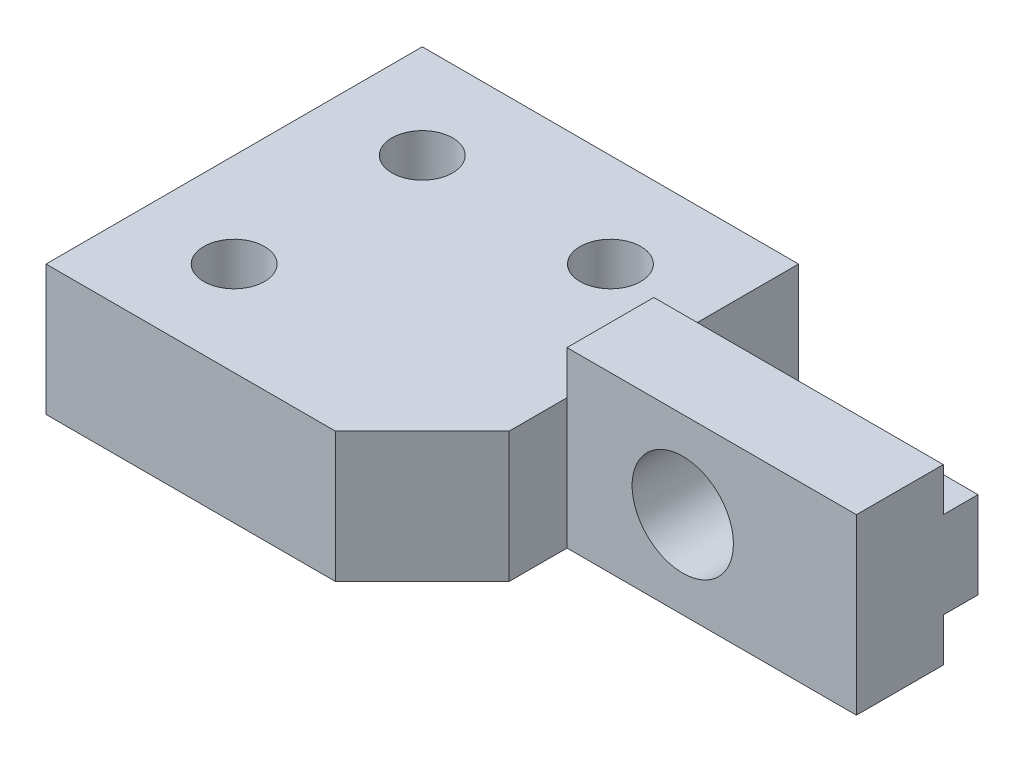
SolidWorks part; units mm, degrees
ref_plane "前视基准面" through (0, 0, 0) normal (0, 0, 1) x (1, 0, 0)
ref_plane "上视基准面" through (0, 0, 0) normal (0, 1, 0) x (1, 0, 0)
ref_plane "右视基准面" through (0, 0, 0) normal (1, 0, 0) x (0, 0, -1)
sketch "草图2" plane through (0, 0, 0) normal (0, 1, 0) x (1, 0, 0)
  line L2 (-3.25, 0) -> (3.25, 0) construction
  line L7 (-6.5, 3.25) -> (6.5, 3.25)
  line L8 (-6.5, 3.25) -> (-6.5, -9.75)
  line L9 (-6.5, -9.75) -> (3.5, -9.75)
  line L11 (6.5, 3.25) -> (6.5, -6.75)
  line L12 (0, 0) -> (0, 3.25) construction
  line L13 (-3.25, -3.25) -> (-6.5, -3.25) construction
  line L14 (3.5, -9.75) -> (6.5, -6.75)
  line L16 (-3.25, -6.5) -> (-3.25, 0) construction
  circle A0 centre (-3.25, 0) radius 1.05
  circle A1 centre (3.25, 0) radius 1.05
  circle A2 centre (-3.25, -6.5) radius 1.05
  point P4 (0, 0)
  dimension "D1" = 2.1
  dimension "D2" = 6.5
  dimension "D3" = 13
  dimension "D4" = 10
  dimension "D5" = 13
extrude "凸台-拉伸1" add sketch "草图2" along normal blind 6
sketch "草图4" plane through (6.5, 0, 11.5) normal (1, 0, 0) x (0, 0, -1)
  line L0 (9.75, 6) -> (9.75, 4.5)
  line L6 (9.75, 4.5) -> (10.95, 4.5)
  line L7 (10.95, 4.5) -> (10.95, 1.5)
  line L8 (10.95, 1.5) -> (9.75, 1.5)
  line L9 (9.75, 1.5) -> (9.75, 0)
  line L10 (4.75, 0) -> (14.75, 0) construction
  line L11 (9.75, 0) -> (6.75, 0)
  line L12 (6.75, 0) -> (6.75, 6)
  line L13 (6.75, 6) -> (9.75, 6)
  line L14 (10.95, 3) -> (14.75, 3) construction
  line L16 (14.75, 6) -> (14.75, 0) construction
  line L17 (14.75, 6) -> (1.75, 6) construction
  point P2 (8.25, 6)
  point P6 (8.25, 6)
  dimension "D1" = 3
  dimension "D2" = 1.2
  dimension "D3" = 3
extrude "凸台-拉伸3" add sketch "草图4" along normal blind 10
sketch "草图5" plane through (0, 0, 4.75) normal (0, 0, 1) x (1, 0, 0)
  line L0 (16.5, 6) -> (16.5, 0) construction
  line L1 (6.5, 6) -> (6.5, 0) construction
  circle A0 centre (10.5, 3) radius 1.75
  point P5 (16.5, 3)
  dimension "D1" = 3.5
  dimension "D2" = 4
extrude "切除-拉伸1" cut sketch "草图5" against normal through all
sketch "草图6" plane through (0, 6, 0) normal (0, 1, 0) x (1, 0, 0)
  line L0 (-6.5, -9.75) -> (3.5, -9.75) construction
  line L1 (-6.5, 3.25) -> (6.5, 3.25)
  line L2 (-6.5, 3.25) -> (-6.5, -9.75)
  line L3 (-6.5, -9.75) -> (6.5, -9.75)
  line L4 (6.5, 3.25) -> (6.5, -9.75)
  line L5 (-6.5, 3.25) -> (-6.5, -9.75) construction
  point P6 (0, 0)
  point P7 (-6.5, -9.75)
extrude "切除-拉伸2" cut sketch "草图6" against normal up to surface (1.5 mm away) up to face at (8.0493, 4.5, 1.15)
